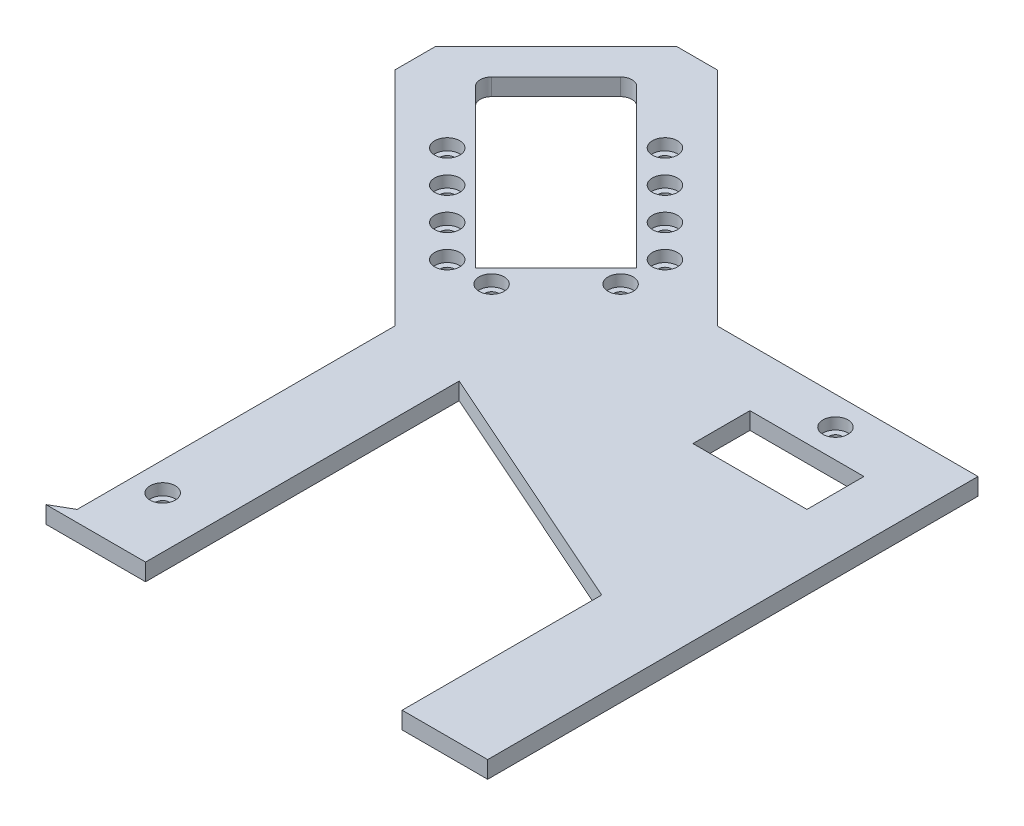
SolidWorks part; units mm, degrees
ref_plane "Front" through (0, 0, 0) normal (0, 0, 1) x (1, 0, 0)
ref_plane "Top" through (0, 0, 0) normal (0, 1, 0) x (1, 0, 0)
ref_plane "Right" through (0, 0, 0) normal (1, 0, 0) x (0, 0, -1)
sketch "草图1" plane through (0, 0, 0) normal (0, 1, 0) x (1, 0, 0)
  line L0 (-45.7157, 114) -> (45.7157, 114)
  line L1 (-74, 0) -> (74, 0) construction
  line L2 (74, -30) -> (91.3205, -20)
  line L3 (91.3205, -20) -> (146.3205, -20)
  line L4 (151.3205, -15) -> (151.3205, 15)
  line L5 (-60, 100) -> (60, -100) construction
  line L6 (-60, -100) -> (60, 100) construction
  line L7 (74, -30) -> (74, -85.7157)
  line L8 (-45.7157, -114) -> (45.7157, -114)
  line L9 (-74, 85.7157) -> (-74, 30)
  line L10 (146.3205, 20) -> (91.3205, 20)
  line L11 (74, 30) -> (91.3205, 20)
  line L12 (0, 100) -> (0, -100) construction
  line L13 (-74, 30) -> (-91.3205, 20)
  line L14 (-146.3205, 20) -> (-91.3205, 20)
  line L15 (-151.3205, -15) -> (-151.3205, 15)
  line L16 (-91.3205, -20) -> (-146.3205, -20)
  line L17 (-74, -30) -> (-91.3205, -20)
  line L18 (-74, -30) -> (-74, -85.7157)
  line L19 (74, 85.7157) -> (74, 30)
  line L20 (91.6777, 152.8909) -> (112.8909, 131.6777)
  line L21 (74, 85.7157) -> (112.8909, 124.6066)
  line L22 (45.7157, 114) -> (84.6066, 152.8909)
  line L23 (-74, 85.7157) -> (-112.8909, 124.6066)
  line L24 (-91.6777, 152.8909) -> (-112.8909, 131.6777)
  line L25 (-45.7157, 114) -> (-84.6066, 152.8909)
  line L26 (74, -85.7157) -> (112.8909, -124.6066)
  line L27 (91.6777, -152.8909) -> (112.8909, -131.6777)
  line L28 (45.7157, -114) -> (84.6066, -152.8909)
  line L29 (-74, -85.7157) -> (-112.8909, -124.6066)
  line L30 (-91.6777, -152.8909) -> (-112.8909, -131.6777)
  line L31 (-45.7157, -114) -> (-84.6066, -152.8909)
  line L32 (-84.6066, 152.8909) -> (-91.6777, 152.8909)
  line L33 (-112.8909, 131.6777) -> (-112.8909, 124.6066)
  line L34 (-151.3205, 15) -> (-146.3205, 20)
  line L35 (-146.3205, -20) -> (-151.3205, -15)
  line L36 (-112.8909, -124.6066) -> (-112.8909, -131.6777)
  line L37 (-84.6066, -152.8909) -> (-91.6777, -152.8909)
  line L38 (84.6066, -152.8909) -> (91.6777, -152.8909)
  line L39 (112.8909, -131.6777) -> (112.8909, -124.6066)
  line L40 (146.3205, -20) -> (151.3205, -15)
  line L41 (151.3205, 15) -> (146.3205, 20)
  line L42 (112.8909, 124.6066) -> (112.8909, 131.6777)
  line L43 (84.6066, 152.8909) -> (91.6777, 152.8909)
  point P0 (0, 0)
  point P12 (74, 30)
  point P16 (74, -30)
extrude "凸台-拉伸1" add sketch "草图1" along normal blind 3
sketch "草图2" plane through (0, 3, 0) normal (0, 1, 0) x (1, 0, 0)
  line L0 (151.3205, 0) -> (87.3942, 0) construction
  line L1 (151.3205, -15) -> (151.3205, 15) construction
  line L2 (103.8205, -10) -> (103.8205, 10)
  line L3 (103.8205, 10) -> (142.8205, 10)
  line L4 (103.8205, -10) -> (142.8205, -10)
  line L7 (144.8205, -15) -> (144.8205, 15)
  line L8 (144.8205, -8) -> (144.8205, 8)
  arc A0 (142.8205, -10) -> (144.8205, -8) centre (142.8205, -8) ccw
  arc A1 (144.8205, 8) -> (142.8205, 10) centre (142.8205, 8) ccw
  point P11 (103.8205, 0)
  dimension "D5" = 6.5
  dimension "D1" = 2
  dimension "D3" = 20
extrude "切除-拉伸1" cut sketch "草图2" against normal up to next
sketch "草图3" plane through (0, 3, 0) normal (0, 1, 0) x (1, 0, 0)
  line L0 (142.8205, 10) -> (103.8205, 10) construction
  line L1 (103.8205, 10) -> (103.8205, -10) construction
  line L2 (151.3205, 0) -> (86.0016, 0) construction
  line L3 (151.3205, -15) -> (151.3205, 15) construction
  point P0 (105.5705, 13.5)
  point P10 (100.3205, 8)
  point P12 (113.5705, 13.5)
  point P13 (121.5705, 13.5)
  point P14 (129.5705, 13.5)
  point P15 (129.5705, -13.5)
  point P16 (121.5705, -13.5)
  point P17 (113.5705, -13.5)
  point P18 (105.5705, -13.5)
  point P19 (100.3205, -8)
  dimension "D1" = 3.5
  dimension "D2" = 1.75
  dimension "D4" = 3.5
  dimension "D5" = 2
  dimension "D3" = 4
hole_wizard "M2 凹头盖螺钉的柱形沉头孔2" positions "3D草图1" profile "草图9" counterbore size "M2" standard "ANSI Metric" end condition through all
sketch3d "3D草图1"
  point P0 (100.3205, 3, -8)
  point P3 (105.5705, 3, -13.5)
  point P6 (113.5705, 3, -13.5)
  point P9 (121.5705, 3, -13.5)
  point P12 (129.5705, 3, -13.5)
  point P15 (100.3205, 3, 8)
  point P18 (105.5705, 3, 13.5)
  point P21 (113.5705, 3, 13.5)
  point P24 (121.5705, 3, 13.5)
  point P27 (129.5705, 3, 13.5)
sketch "草图9" plane through (100.3205, 3, -8) normal (1, 0, 0) x (0, 0, 1)
  line L0 (0, 0) -> (0, 3)
  line L1 (0, 3) -> (1.2, 3)
  line L3 (1.2, 3) -> (1.2, 2)
  line L4 (1.2, 2) -> (2.2, 2)
  line L5 (2.2, 2) -> (2.2, 0)
  line L7 (2.2, 0) -> (0, 0)
  line L11 (0, -6.35) -> (0, 107.95) construction
  dimension "通孔孔直径" = 2.4
  dimension "通孔孔深度" = 3
  dimension "柱形沉头孔直径" = 4.4
  dimension "柱形沉头孔深度" = 2
sketch "草图10" plane through (0, 3, 0) normal (0, 1, 0) x (1, 0, 0)
  line L0 (102.2843, 142.2843) -> (57.3662, 97.3662) construction
  line L1 (112.8909, 131.6777) -> (91.6777, 152.8909) construction
  line L2 (75.7678, 101.6256) -> (61.6256, 115.7678)
  line L3 (61.6256, 115.7678) -> (79.9162, 134.0583)
  line L4 (75.7678, 101.6256) -> (94.0583, 119.9162)
  line L5 (97.6881, 137.6881) -> (103.3449, 132.0312)
  line L6 (94.0583, 119.9162) -> (103.3449, 129.2028)
  line L7 (79.9162, 134.0583) -> (89.2028, 143.3449)
  line L8 (92.0312, 143.3449) -> (97.6881, 137.6881)
  arc A0 (103.3449, 129.2028) -> (103.3449, 132.0312) centre (101.9307, 130.617) ccw
  arc A1 (92.0312, 143.3449) -> (89.2028, 143.3449) centre (90.617, 141.9307) ccw
  point P9 (68.6967, 108.6967)
  dimension "D1" = 6.5
  dimension "D2" = 2
extrude "切除-拉伸2" cut sketch "草图10" against normal up to next
sketch "草图16" plane through (0, 3, 0) normal (0, 1, 0) x (1, 0, 0)
  line L0 (102.2843, 142.2843) -> (58.019, 98.019) construction
  line L1 (112.8909, 131.6777) -> (91.6777, 152.8909) construction
  line L2 (61.6256, 115.7678) -> (75.7678, 101.6256) construction
  line L3 (89.2028, 143.3449) -> (61.6256, 115.7678) construction
  line L4 (60.3882, 119.4801) -> (80.2149, 139.3067) construction
  point P0 (60.3882, 119.4801)
  point P1 (60.565, 111.8787)
  point P12 (66.045, 125.1369)
  point P13 (71.7019, 130.7938)
  point P14 (77.3588, 136.4506)
  point P15 (96.4506, 117.3588)
  point P16 (90.7938, 111.7019)
  point P17 (85.1369, 106.045)
  point P18 (79.4801, 100.3882)
  point P19 (71.8787, 100.565)
  dimension "D1" = 3.5
  dimension "D2" = 2
  dimension "D3" = 1.75
  dimension "D4" = 3.5
  dimension "D5" = 8
  dimension "D6" = 8
  dimension "D7" = 8
hole_wizard "M2 凹头盖螺钉的柱形沉头孔3" positions "3D草图3" profile "草图17" counterbore size "M2" standard "ANSI Metric" end condition through all
sketch3d "3D草图3"
  point P0 (60.3882, 3, -119.4801)
  point P3 (66.045, 3, -125.1369)
  point P6 (71.7019, 3, -130.7938)
  point P9 (77.3588, 3, -136.4506)
  point P12 (60.565, 3, -111.8787)
  point P15 (71.8787, 3, -100.565)
  point P18 (79.4801, 3, -100.3882)
  point P21 (85.1369, 3, -106.045)
  point P24 (90.7938, 3, -111.7019)
  point P27 (96.4506, 3, -117.3588)
sketch "草图17" plane through (60.3882, 3, -119.4801) normal (1, 0, 0) x (0, 0, 1)
  line L0 (0, 0) -> (0, 3)
  line L1 (0, 3) -> (1.2, 3)
  line L3 (1.2, 3) -> (1.2, 2)
  line L4 (1.2, 2) -> (2.2, 2)
  line L5 (2.2, 2) -> (2.2, 0)
  line L7 (2.2, 0) -> (0, 0)
  line L11 (0, -6.35) -> (0, 107.95) construction
  dimension "通孔孔直径" = 2.4
  dimension "通孔孔深度" = 3
  dimension "柱形沉头孔直径" = 4.4
  dimension "柱形沉头孔深度" = 2
mirror "镜向5" about plane through (0, 0, 0) normal (1, 0, 0) of "切除-拉伸1", "M2 凹头盖螺钉的柱形沉头孔2"
mirror "镜向6" about plane through (0, 0, 0) normal (1, 0, 0) of "切除-拉伸2", "M2 凹头盖螺钉的柱形沉头孔3"
mirror "镜向7" about plane through (0, 0, 0) normal (0, 0, 1) of "切除-拉伸2", "M2 凹头盖螺钉的柱形沉头孔3", "镜向6"
sketch "草图18" plane through (0, 3, 0) normal (0, 1, 0) x (1, 0, 0)
  line L0 (0, 114) -> (0, -114) construction
  line L1 (45.7157, 114) -> (-45.7157, 114) construction
  line L2 (-45.7157, -114) -> (45.7157, -114) construction
  line L3 (-151.3205, 0) -> (151.3205, 0) construction
  line L4 (-151.3205, 15) -> (-151.3205, -15) construction
  line L5 (-60, -28) -> (-15, -28)
  line L6 (-15, -28) -> (-15, -63)
  line L7 (-15, -63) -> (-60, -83)
  line L8 (-60, -83) -> (-60, -28)
  line L12 (10, -94) -> (30, -94)
  line L13 (-10, -94) -> (-30, -94)
  line L14 (-10, -94) -> (-10, -104)
  line L15 (-10, -104) -> (-30, -104)
  line L16 (-30, -94) -> (-30, -104)
  line L17 (-10, -94) -> (-30, -104) construction
  line L18 (-10, -104) -> (-30, -94) construction
  line L19 (10, -104) -> (30, -104)
  line L20 (10, -94) -> (10, -104)
  line L21 (30, -94) -> (30, -104)
  line L22 (15, -63) -> (60, -83)
  line L23 (60, -83) -> (60, -28)
  line L25 (15, -28) -> (15, -63)
  line L26 (60, -28) -> (15, -28)
  line L27 (-10, 104) -> (-30, 104)
  line L28 (-30, 94) -> (-30, 104)
  line L29 (-10, 94) -> (-30, 94)
  line L30 (-10, 94) -> (-10, 104)
  line L31 (30, 94) -> (30, 104)
  line L32 (10, 104) -> (30, 104)
  line L33 (10, 94) -> (10, 104)
  line L34 (10, 94) -> (30, 94)
  line L35 (15, 63) -> (60, 83)
  line L36 (60, 83) -> (60, 28)
  line L37 (60, 28) -> (15, 28)
  line L38 (15, 28) -> (15, 63)
  line L39 (-15, 28) -> (-15, 63)
  line L40 (-60, 28) -> (-15, 28)
  line L41 (-60, 83) -> (-60, 28)
  line L42 (-15, 63) -> (-60, 83)
  point P17 (-20, -99)
  point P32 (0, -20)
  point P33 (0, -10)
  dimension "D5" = 60
  dimension "D6" = 45
  dimension "D7" = 55
  dimension "D8" = 35
  dimension "D9" = 20
  dimension "D10" = 10
  dimension "D11" = 10
  dimension "D12" = 10
extrude "切除-拉伸3" cut sketch "草图18" against normal up to next
sketch "草图19" plane through (0, 3, 0) normal (0, 1, 0) x (1, 0, 0)
  line L0 (0, 114) -> (0, -114) construction
  line L1 (45.7157, 114) -> (-45.7157, 114) construction
  line L2 (-45.7157, -114) -> (45.7157, -114) construction
  line L3 (-151.3205, 0) -> (151.3205, 0) construction
  line L4 (-151.3205, 15) -> (-151.3205, -15) construction
  line L5 (-10, 94) -> (-10, 104) construction
  point P0 (-20, 109)
  point P14 (20, 109)
  point P15 (20, -109)
  point P16 (-20, -109)
  point P17 (-20, 0)
  point P18 (20, 0)
  dimension "D1" = 5
  dimension "D2" = 10
hole_wizard "M2 凹头盖螺钉的柱形沉头孔4" positions "3D草图4" profile "草图20" counterbore size "M2" standard "ANSI Metric" end condition through all
sketch3d "3D草图4"
  point P0 (-20, 3, 109)
  point P3 (20, 3, 109)
  point P6 (-20, 3, -109)
  point P9 (20, 3, -109)
sketch "草图20" plane through (-20, 3, 109) normal (1, 0, 0) x (0, 0, 1)
  line L0 (0, 0) -> (0, 3)
  line L1 (0, 3) -> (1.2, 3)
  line L3 (1.2, 3) -> (1.2, 2)
  line L4 (1.2, 2) -> (2.2, 2)
  line L5 (2.2, 2) -> (2.2, 0)
  line L7 (2.2, 0) -> (0, 0)
  line L11 (0, -6.35) -> (0, 107.95) construction
  dimension "通孔孔直径" = 2.4
  dimension "通孔孔深度" = 3
  dimension "柱形沉头孔直径" = 4.4
  dimension "柱形沉头孔深度" = 2
sketch "草图21" plane through (0, 3, 0) normal (0, 1, 0) x (1, 0, 0)
  line L0 (-74, 85.7157) -> (-74, 30) construction
  line L1 (74, 30) -> (74, 85.7157) construction
  line L2 (-60, 28) -> (-15, 28) construction
  line L3 (15, 28) -> (60, 28) construction
  point P0 (-69, 40)
  point P1 (69, 40)
  point P6 (-69, 0)
  point P11 (69, 0)
  dimension "D1" = 5
  dimension "D2" = 5
  dimension "D3" = 12
  dimension "D4" = 12
  dimension "D5" = 40
hole_wizard "M2 凹头盖螺钉的柱形沉头孔5" positions "3D草图5" profile "草图22" counterbore size "M2" standard "ANSI Metric" end condition through all
sketch3d "3D草图5"
  point P0 (-69, 3, -40)
  point P3 (69, 3, -40)
sketch "草图22" plane through (-69, 3, -40) normal (1, 0, 0) x (0, 0, 1)
  line L0 (0, 0) -> (0, 3)
  line L1 (0, 3) -> (1.2, 3)
  line L3 (1.2, 3) -> (1.2, 2)
  line L4 (1.2, 2) -> (2.2, 2)
  line L5 (2.2, 2) -> (2.2, 0)
  line L7 (2.2, 0) -> (0, 0)
  line L11 (0, -6.35) -> (0, 107.95) construction
  dimension "通孔孔直径" = 2.4
  dimension "通孔孔深度" = 3
  dimension "柱形沉头孔直径" = 4.4
  dimension "柱形沉头孔深度" = 2
mirror "镜向8" about plane through (0, 0, 0) normal (0, 0, 1) of "M2 凹头盖螺钉的柱形沉头孔5"
hole_wizard "M2 凹头盖螺钉的柱形沉头孔6" positions "3D草图6" profile "草图23" counterbore size "M2" standard "ANSI Metric" end condition through all
sketch3d "3D草图6"
  point P0 (-69, 3, 0)
  point P3 (69, 3, 0)
sketch "草图23" plane through (-69, 3, 0) normal (1, 0, 0) x (0, 0, 1)
  line L0 (0, 0) -> (0, 3)
  line L1 (0, 3) -> (1.2, 3)
  line L3 (1.2, 3) -> (1.2, 2)
  line L4 (1.2, 2) -> (2.2, 2)
  line L5 (2.2, 2) -> (2.2, 0)
  line L7 (2.2, 0) -> (0, 0)
  line L11 (0, -6.35) -> (0, 107.95) construction
  dimension "通孔孔直径" = 2.4
  dimension "通孔孔深度" = 3
  dimension "柱形沉头孔直径" = 4.4
  dimension "柱形沉头孔深度" = 2
sketch "草图24" plane through (0, 3, 0) normal (0, 1, 0) x (1, 0, 0)
  line L3 (-10, 28) -> (10, 28)
  line L4 (-10, 28) -> (-10, -28)
  line L5 (-10, -28) -> (10, -28)
  line L6 (10, 28) -> (10, -28)
  line L7 (-10, 28) -> (10, -28) construction
  line L8 (-10, -28) -> (10, 28) construction
  point P0 (0, 0)
  dimension "D1" = 20
  dimension "D2" = 56
extrude "切除-拉伸4" cut sketch "草图24" against normal blind 10
hole_wizard "M2 凹头盖螺钉的柱形沉头孔7" positions "3D草图7" profile "草图25" counterbore size "M2" standard "ANSI Metric" end condition through all
sketch3d "3D草图7"
  point P0 (-20, 3, 0)
  point P3 (20, 3, 0)
sketch "草图25" plane through (-20, 3, 0) normal (1, 0, 0) x (0, 0, 1)
  line L0 (0, 0) -> (0, 3)
  line L1 (0, 3) -> (1.2, 3)
  line L3 (1.2, 3) -> (1.2, 2)
  line L4 (1.2, 2) -> (2.2, 2)
  line L5 (2.2, 2) -> (2.2, 0)
  line L7 (2.2, 0) -> (0, 0)
  line L11 (0, -6.35) -> (0, 107.95) construction
  dimension "通孔孔直径" = 2.4
  dimension "通孔孔深度" = 3
  dimension "柱形沉头孔直径" = 4.4
  dimension "柱形沉头孔深度" = 2
sketch "草图26" plane through (0, 3, 0) normal (0, 1, 0) x (1, 0, 0)
  line L0 (10, 28) -> (-10, 28) construction
  line L1 (0, 28) -> (-112.8909, 28)
  line L2 (0, 28) -> (0, 152.8909)
  line L3 (0, 152.8909) -> (-112.8909, 152.8909)
  line L4 (-112.8909, 28) -> (-112.8909, 152.8909)
extrude "切除-拉伸5" cut sketch "草图26" against normal blind 10 flip side to cut
